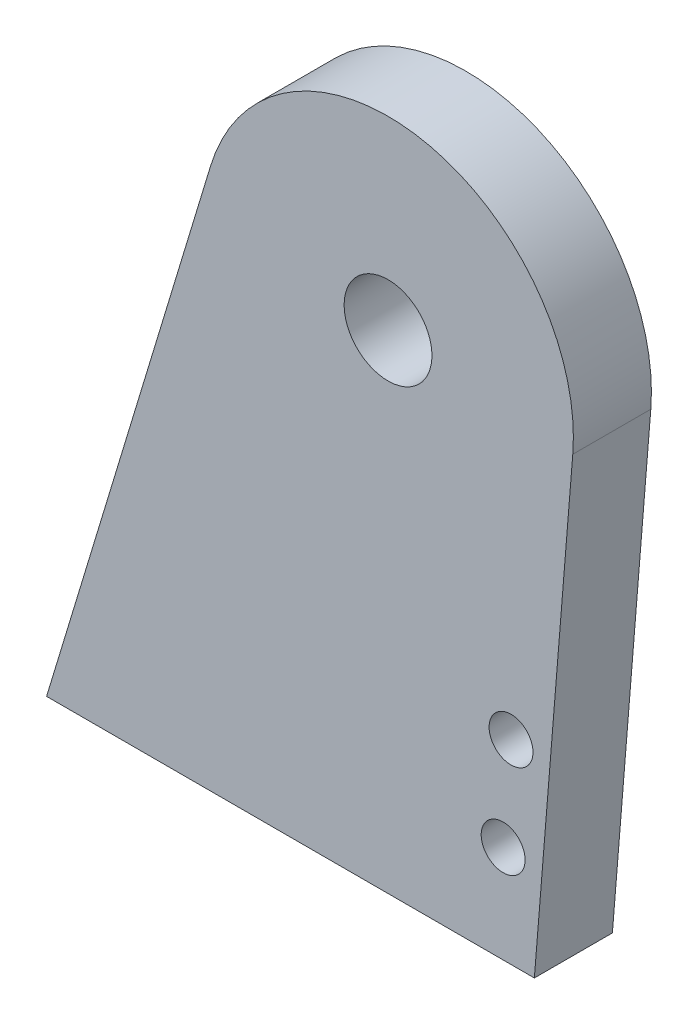
SolidWorks part; units mm, degrees
material "5052-O"
ref_plane "정면" through (0, 0, 0) normal (0, 0, 1) x (1, 0, 0)
ref_plane "윗면" through (0, 0, 0) normal (0, 1, 0) x (1, 0, 0)
ref_plane "우측면" through (0, 0, 0) normal (1, 0, 0) x (0, 0, -1)
sketch "스케치1" plane through (0, 0, 0) normal (0, 0, 1) x (1, 0, 0)
  line L0 (0, 0) -> (50, 0)
  line L1 (50, 0) -> (53.9376, 48.4613)
  line L2 (0, 0) -> (16.8161, 55.5087)
  circle A0 centre (35, 50) radius 19
  dimension "D1" = 38
  dimension "D2" = 50
  dimension "D3" = 50
  dimension "D5" = 15
extrude "보스-돌출1" add sketch "스케치1" along normal blind 8
hole_wizard "M4 여유 구멍1" positions "스케치2" profile "스케치3" hole size "M4" standard "ISO" end condition up to next
sketch "스케치2" plane through (0, 0, 8) normal (0, 0, 1) x (1, 0, 0)
  line L0 (47.6092, 19.9672) -> (46.7993, 10)
  line L2 (50, 0) -> (53.9376, 48.4613) construction
  line L3 (0, 0) -> (50, 0) construction
  point P0 (46.7993, 10)
  point P2 (47.6092, 19.9672)
  dimension "D1" = 10
  dimension "D2" = 4
  dimension "D3" = 10
sketch "스케치3" plane through (46.7993, 10, 8) normal (1, 0, 0) x (0, -1, 0)
  line L0 (0, 0) -> (0, 8)
  line L1 (0, 8) -> (2.25, 8)
  line L2 (2.25, 8) -> (2.25, 0)
  line L5 (2.25, 0) -> (0, 0)
  line L11 (0, -6.35) -> (0, 107.95) construction
  dimension "관통 구멍 지름" = 4.5
  dimension "관통 구멍 깊이" = 8
hole_wizard "M3 나사 구멍1" positions "스케치4" profile "스케치5" tap size "M3" standard "ISO"
sketch "스케치4" plane through (0, 0, 0) normal (0, -1, 0) x (-1, 0, 0)
  line L0 (-10, -4) -> (-40, -4)
  line L2 (0, 0) -> (-50, 0) construction
  line L3 (-50, -8) -> (-50, 0) construction
  point P0 (-10, -4)
  point P2 (-40, -4)
  point P8 (-25, -4)
  point P11 (-25, 0)
  point P14 (-50, -4)
  dimension "D1" = 30
sketch "스케치5" plane through (10, 0, 4) normal (1, 0, 0) x (0, 0, -1)
  line L0 (0, 0) -> (0, 9.2511)
  line L1 (0, 9.2511) -> (1.25, 8.5)
  line L2 (1.25, 8.5) -> (1.25, 0.275)
  line L3 (1.25, 0.275) -> (1.525, 0)
  line L5 (1.525, 0) -> (0, 0)
  line L6 (-1.25, 0.275) -> (-1.525, 0) construction
  line L10 (0, 9.2511) -> (-1.25, 8.5) construction
  line L11 (0, -6.35) -> (0, 107.95) construction
  dimension "탭 드릴 지름" = 2.5
  dimension "탭 드릴 깊이" = 8.5
  dimension "표면 카운터싱크 지름" = 3.05
  dimension "표면 카운터싱크 각도" = 90
  dimension "드릴 각도" = 118
cosmetic thread "구멍 나사산1" parameters "D1"=6, "D2"=3
cosmetic thread "구멍 나사산2" parameters "D1"=6, "D2"=3
hole_wizard "M8 여유 구멍1" positions "스케치6" profile "스케치7" hole size "M8" standard "ISO" end condition through all
sketch "스케치6" plane through (0, 0, 0) normal (0, 0, -1) x (-1, 0, 0)
  point P0 (-35, 50)
sketch "스케치7" plane through (35, 50, 0) normal (1, 0, 0) x (0, 1, 0)
  line L0 (0, 0) -> (0, 8)
  line L1 (0, 8) -> (4.5, 8)
  line L2 (4.5, 8) -> (4.5, 0)
  line L5 (4.5, 0) -> (0, 0)
  line L11 (0, -6.35) -> (0, 107.95) construction
  dimension "관통 구멍 지름" = 9
  dimension "관통 구멍 깊이" = 8
